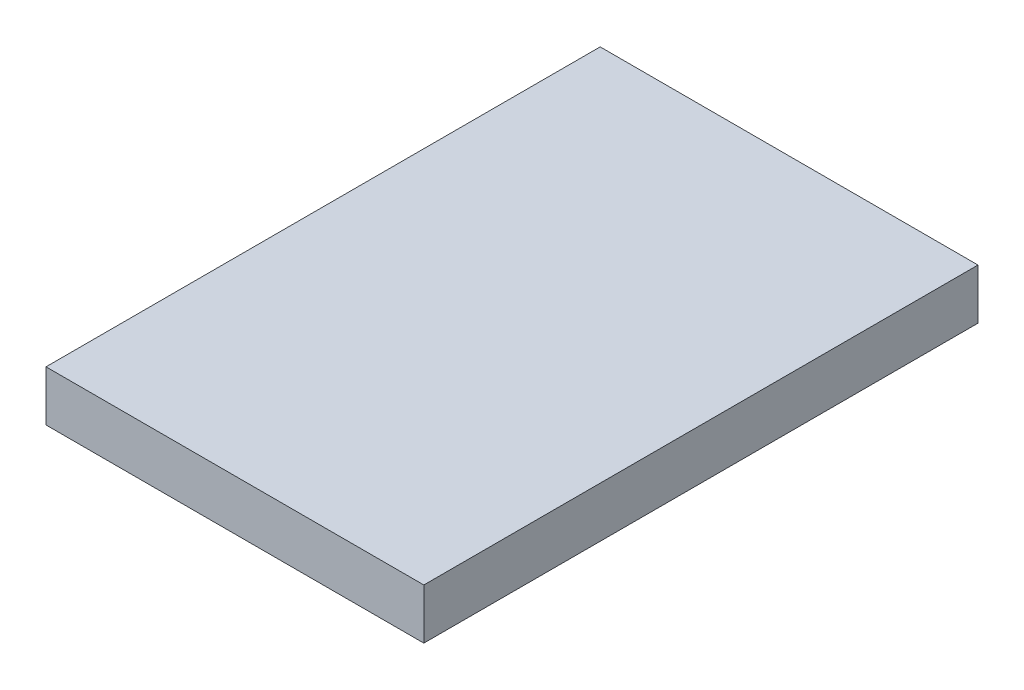
SolidWorks part; units mm, degrees
material "Керамика фарфор"
ref_plane "Спереди" through (0, 0, 0) normal (0, 0, 1) x (1, 0, 0)
ref_plane "Сверху" through (0, 0, 0) normal (0, 1, 0) x (1, 0, 0)
ref_plane "Справа" through (0, 0, 0) normal (1, 0, 0) x (0, 0, -1)
sketch "Эскиз1" plane through (0, 0, 0) normal (0, 1, 0) x (1, 0, 0)
  line L1 (0, 0) -> (75, 0)
  line L2 (0, 0) -> (0, 110)
  line L3 (0, 110) -> (75, 110)
  line L4 (75, 0) -> (75, 110)
  dimension "D1" = 75
  dimension "D2" = 110
extrude "Бобышка-Вытянуть1" add sketch "Эскиз1" along normal blind 10
